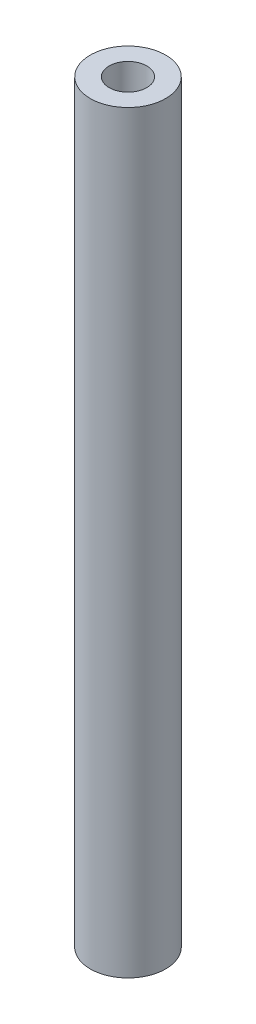
SolidWorks part; units mm, degrees
ref_plane "前视基准面" through (0, 0, 0) normal (0, 0, 1) x (1, 0, 0)
ref_plane "上视基准面" through (0, 0, 0) normal (0, 1, 0) x (1, 0, 0)
ref_plane "右视基准面" through (0, 0, 0) normal (1, 0, 0) x (0, 0, -1)
sketch "草图2" plane through (0, 0, 0) normal (0, 1, 0) x (1, 0, 0)
  circle A0 centre (0, 0) radius 4
  dimension "D1" = 8
extrude "凸台-拉伸1" add sketch "草图2" along normal blind 80
sketch "草图3" plane through (0, 80, 0) normal (0, 1, 0) x (1, 0, 0)
  circle A0 centre (0, 0) radius 2
  dimension "D1" = 4
extrude "切除-拉伸1" cut sketch "草图3" against normal through all
